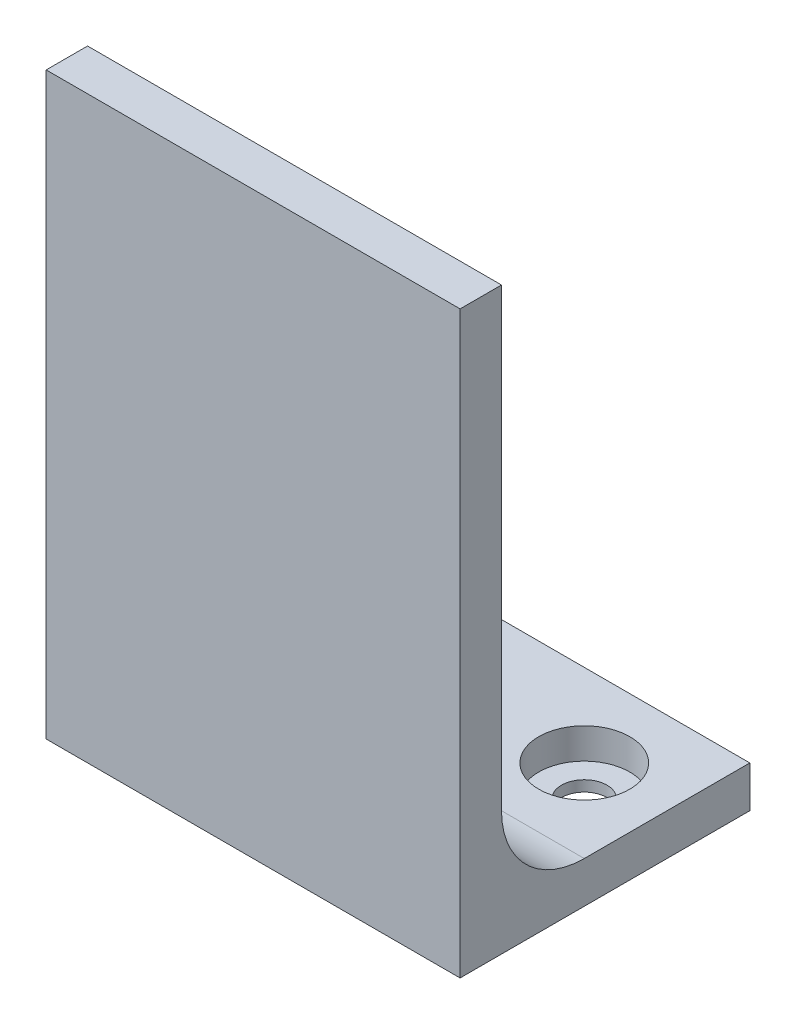
SolidWorks part; units mm, degrees
ref_plane "Front Plane" through (0, 0, 0) normal (0, 0, 1) x (1, 0, 0)
ref_plane "Top Plane" through (0, 0, 0) normal (0, 1, 0) x (1, 0, 0)
ref_plane "Right Plane" through (0, 0, 0) normal (1, 0, 0) x (0, 0, -1)
sketch "Sketch2" plane through (0, 0, 0) normal (1, 0, 0) x (0, 0, -1)
  line L0 (0, 0) -> (0, 70)
  line L1 (0, 70) -> (5, 70)
  line L2 (5, 70) -> (5, 15)
  line L3 (15, 5) -> (35, 5)
  line L4 (35, 5) -> (35, 0)
  line L5 (35, 0) -> (0, 0)
  arc A0 (5, 15) -> (15, 5) centre (15, 15) ccw
  dimension "D5" = 10
  dimension "D1" = 5
  dimension "D2" = 5
  dimension "D3" = 70
  dimension "D4" = 35
extrude "Boss-Extrude1" add sketch "Sketch2" along normal blind 50
sketch "Sketch3" plane through (0, 5, 0) normal (0, 1, 0) x (1, 0, 0)
  line L0 (0, 25) -> (50, 25) construction
  line L1 (0, 35) -> (0, 15) construction
  line L2 (50, 35) -> (50, 15) construction
  circle A0 centre (10, 25) radius 2.5
  circle A1 centre (40, 25) radius 2.5
  point P6 (10, 25)
  point P8 (40, 25)
  dimension "D1" = 5
  dimension "D2" = 5
  dimension "D3" = 10
  dimension "D4" = 10
hole_wizard "CBORE for M5 Pan Head Screw1" positions "Sketch3" profile "Sketch4" counterbore size "M5" standard "ISO"
sketch "Sketch4" plane through (40, 5, -25) normal (1, 0, 0) x (0, 0, 1)
  line L0 (0, 0) -> (0, 31.6524)
  line L1 (0, 31.6524) -> (2.75, 30)
  line L2 (2.75, 30) -> (2.75, 3.7)
  line L3 (2.75, 3.7) -> (5.5, 3.7)
  line L4 (5.5, 3.7) -> (5.5, 0)
  line L5 (5.5, 0) -> (0, 0)
  line L10 (0, 31.6524) -> (-2.75, 30) construction
  line L11 (0, -6.35) -> (0, 107.95) construction
  dimension "Hole Dia." = 5.5
  dimension "Hole Depth" = 30
  dimension "C'Bore Dia." = 11
  dimension "C'Bore Depth" = 3.7
  dimension "Drill Angle" = 118
